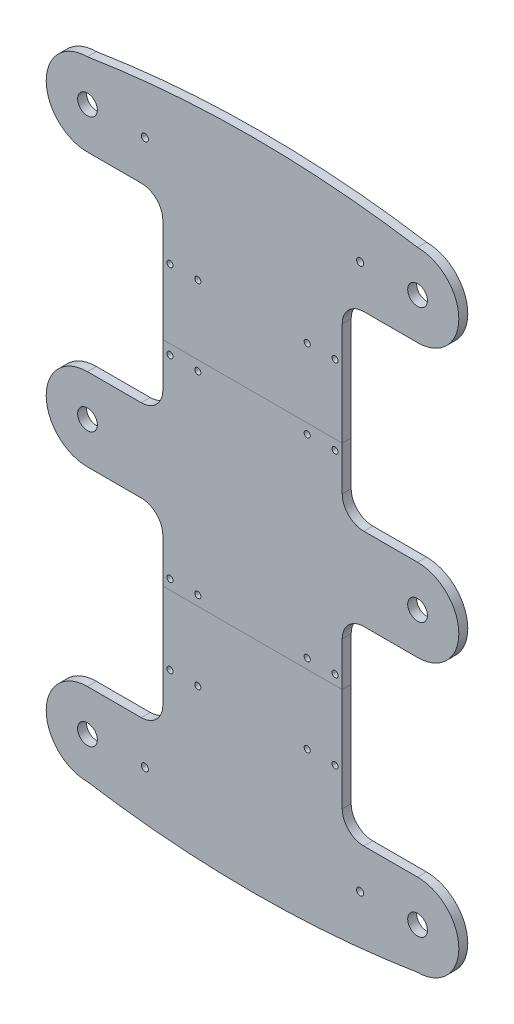
SolidWorks part; units mm, degrees
ref_plane "Płaszczyzna przednia" through (0, 0, 0) normal (0, 0, 1) x (1, 0, 0)
ref_plane "Płaszczyzna górna" through (0, 0, 0) normal (0, 1, 0) x (1, 0, 0)
ref_plane "Płaszczyzna prawa" through (0, 0, 0) normal (1, 0, 0) x (0, 0, -1)
sketch "Szkic1" plane through (0, 0, 0) normal (0, 0, 1) x (1, 0, 0)
  line L0 (-203.4983, 203.4983) -> (200.3017, -200.3017) construction
  line L5 (-225.8431, 0) -> (204.6382, 0) construction
  line L6 (0, 259.0582) -> (0, -261.5805) construction
  line L7 (202.2417, 202.2417) -> (-202.2417, -202.2417) construction
  line L9 (-95, 116) -> (-57, 116) construction
  line L10 (-95, 116) -> (-95, 36) construction
  line L11 (-95, 36) -> (-57, 36) construction
  line L12 (-57, 116) -> (-57, 36) construction
  line L28 (-50, -116.999) -> (-50, -35.001)
  line L29 (50, -116.999) -> (50, -35.001)
  line L31 (-95, 116) -> (-57, 36) construction
  line L32 (-57, 116) -> (-95, 36) construction
  line L33 (-62, -23.001) -> (-92, -23.001)
  line L38 (-50, 35.001) -> (-50, 116.999)
  line L39 (-62, 23.001) -> (-92, 23.001)
  line L42 (50, 35.001) -> (50, 116.999)
  line L43 (-112.0619, 76) -> (134.9818, 76) construction
  line L44 (-112.0619, -76) -> (134.9818, -76) construction
  line L46 (-62, 128.999) -> (-92, 128.999)
  line L48 (-62, -128.999) -> (-92, -128.999)
  line L53 (62, -128.999) -> (92, -128.999)
  line L54 (62, 23.001) -> (92, 23.001)
  line L55 (62, -23.001) -> (92, -23.001)
  line L57 (62, 128.999) -> (92, 128.999)
  arc A19 (-92, 23.001) -> (-92, -23.001) centre (-92, 0) ccw
  arc A20 (-62, -23.001) -> (-50, -35.001) centre (-62, -35.001) cw
  arc A21 (-62, 23.001) -> (-50, 35.001) centre (-62, 35.001) ccw
  arc A34 (-92, 128.999) -> (-92, 175.001) centre (-92, 152) cw
  arc A35 (-62, 128.999) -> (-50, 116.999) centre (-62, 116.999) cw
  arc A39 (-62, -128.999) -> (-50, -116.999) centre (-62, -116.999) ccw
  arc A40 (-92, -175.001) -> (-92, -128.999) centre (-92, -152) cw
  arc A41 (62, -128.999) -> (50, -116.999) centre (62, -116.999) cw
  arc A42 (92, -175.001) -> (92, -128.999) centre (92, -152) ccw
  arc A47 (62, -23.001) -> (50, -35.001) centre (62, -35.001) ccw
  arc A48 (62, 23.001) -> (50, 35.001) centre (62, 35.001) cw
  arc A50 (92, 23.001) -> (92, -23.001) centre (92, 0) cw
  arc A55 (62, 128.999) -> (50, 116.999) centre (62, 116.999) ccw
  arc A56 (92, 128.999) -> (92, 175.001) centre (92, 152) ccw
  arc A61 (-92, 175.001) -> (92, 175.001) centre (0, -400.8456) cw
  arc A62 (-92, -175.001) -> (92, -175.001) centre (0, 400.8456) ccw
  point P0 (0, 0)
  point P30 (0, 175.001)
  point P32 (50, 0)
  point P33 (-50, 0)
  point P55 (-76, 76)
  point P60 (-50, -23.001)
  point P63 (-50, 23.001)
  point P65 (-57, 76)
  dimension "D9" = 12
  dimension "D10" = 583.1495
  dimension "D1" = 45
  dimension "D2" = 45
  dimension "D3" = 38
  dimension "D4" = 80
  dimension "D8" = 100
  dimension "D14" = 7
extrude "Dodanie-wyciągnięcie1" add sketch "Szkic1" along normal blind 5
sketch "Szkic2" plane through (-50, 0, 0) normal (-1, 0, 0) x (0, 0, 1)
  line L0 (-4.6021, 76) -> (9.4932, 76) construction
  line L1 (-7.082, -76) -> (18.5034, -76) construction
sketch "Szkic3" plane through (0, 0, 5) normal (0, 0, 1) x (1, 0, 0)
  line L0 (0, -223.0773) -> (0, 267.3344) construction
  line L1 (-158.5168, 0) -> (193.5752, 0) construction
  line L2 (-50, 76) -> (50, 76) construction
  line L3 (-50, 116.999) -> (-50, 35.001) construction
  line L4 (50, 35.001) -> (50, 116.999) construction
  line L5 (-50, -76) -> (50, -76) construction
  line L6 (-50, -35.001) -> (-50, -116.999) construction
  line L7 (50, -116.999) -> (50, -35.001) construction
  circle A1 centre (92, 0) radius 5.5
  circle A14 centre (-92, 0) radius 5.5
  circle A15 centre (92, 152) radius 5.5
  circle A16 centre (-92, 152) radius 5.5
  circle A17 centre (92, -152) radius 5.5
  circle A18 centre (-92, -152) radius 5.5
  dimension "D1" = 92
  dimension "D2" = 11
extrude "Wytnij-wyciągnięcie1" cut sketch "Szkic3" against normal through all
sketch "Szkic5" plane through (0, 0, 5) normal (0, 0, 1) x (1, 0, 0)
  line L0 (-28.175, 59.0941) -> (-28.175, 59.908) construction
  line L1 (-139.0421, 59.501) -> (82.6921, 59.501) construction
  line L2 (0, 203.7169) -> (0, -223.8) construction
  line L3 (-188.5606, 0) -> (309.2441, 0) construction
  line L4 (-50, 116.999) -> (-50, 35.001) construction
  line L5 (-120.1674, -152) -> (10.35, -152) construction
  line L6 (-62, -122.1507) -> (-62, -181.8493) construction
  line L7 (-50, 76) -> (50, 76) construction
  line L8 (50, 35.001) -> (50, 116.999) construction
  line L9 (-38.25, 104.5097) -> (-38.25, 44.7993) construction
  line L10 (-28.175, -59.0941) -> (-28.175, -59.908) construction
  circle A3 centre (-46, 54.001) radius 1.7
  circle A16 centre (-60, -152) radius 2
  circle A17 centre (60, -152) radius 2
  circle A18 centre (60, 152) radius 2
  circle A19 centre (-60, 152) radius 2
  circle A25 centre (-46, 97.999) radius 1.7
  circle A26 centre (-30.5, 97.999) radius 1.7
  circle A27 centre (-30.5, 54.001) radius 1.7
  circle A28 centre (46, 54.001) radius 1.7
  circle A29 centre (30.5, 54.001) radius 1.7
  circle A30 centre (46, 97.999) radius 1.7
  circle A31 centre (30.5, 97.999) radius 1.7
  circle A32 centre (-30.5, -54.001) radius 1.7
  circle A33 centre (-30.5, -97.999) radius 1.7
  circle A34 centre (-46, -97.999) radius 1.7
  circle A35 centre (-46, -54.001) radius 1.7
  circle A36 centre (30.5, -97.999) radius 1.7
  circle A37 centre (46, -97.999) radius 1.7
  circle A38 centre (30.5, -54.001) radius 1.7
  circle A39 centre (46, -54.001) radius 1.7
  point P4 (-28.175, 59.501)
  point P5 (-28.175, 59.501)
  dimension "D2" = 3.4
  dimension "D6" = 4
  dimension "D11" = 5.5
  dimension "D3" = 4
  dimension "D4" = 16.499
  dimension "D5" = 7.75
  dimension "D7" = 2
extrude "Wytnij-wyciągnięcie2" cut sketch "Szkic5" against normal through all
sketch "Szkic6" plane through (0, 0, 5) normal (0, 0, 1) x (1, 0, 0)
  line L0 (-67.576, 59.5) -> (69.0293, 59.5)
  line L1 (-127.1592, 0) -> (151.8644, 0) construction
  line L2 (-67.576, -59.5) -> (69.0293, -59.5)
  circle A0 centre (92, 0) radius 5.5 construction
  dimension "D1" = 59.5
split "Podziel1" trim tools "Szkic6" bodies to split 103 resulting bodies 109 110 111
